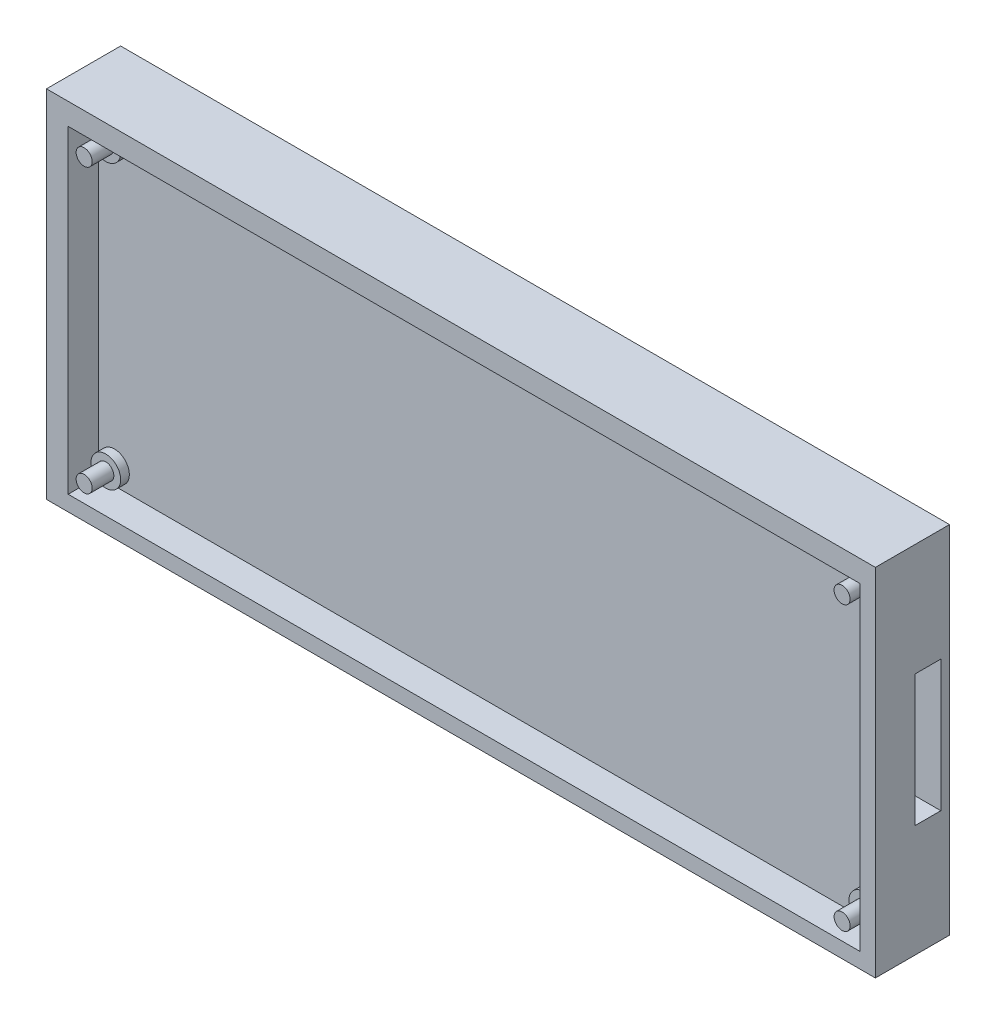
SolidWorks part; units mm, degrees
ref_plane "Front Plane" through (0, 0, 0) normal (0, 0, 1) x (1, 0, 0)
ref_plane "Top Plane" through (0, 0, 0) normal (0, 1, 0) x (1, 0, 0)
ref_plane "Right Plane" through (0, 0, 0) normal (1, 0, 0) x (0, 0, -1)
sketch "Sketch1" plane through (0, 0, 0) normal (0, 0, 1) x (1, 0, 0)
  line L1 (-101.6249, 55.2181) -> (80.9503, 55.2181)
  line L2 (-101.6249, 55.2181) -> (-101.6249, -18.2387)
  line L3 (-101.6249, -18.2387) -> (80.9503, -18.2387)
  line L4 (80.9503, 55.2181) -> (80.9503, -18.2387)
extrude "Boss-Extrude1" add sketch "Sketch1" along normal blind 5 and the other way blind 0.0932
sketch "Sketch2" plane through (0, 0, 5) normal (0, 0, 1) x (1, 0, 0)
  circle A0 centre (-97.9419, 50.9509) radius 3.4164
  circle A1 centre (76.8101, 50.9509) radius 3.4164
  circle A2 centre (76.8101, -14.2763) radius 3.4164
  circle A3 centre (-97.9419, -14.2763) radius 3.4164
extrude "Boss-Extrude2" add sketch "Sketch2" along normal blind 7
sketch "Sketch3" plane through (0, 0, 12) normal (0, 0, 1) x (1, 0, 0)
  circle A0 centre (-97.9419, 50.9509) radius 1.85
  circle A1 centre (-97.9419, -14.2763) radius 1.85
  circle A2 centre (76.8101, -14.2763) radius 1.85
  circle A3 centre (76.8101, 50.9509) radius 1.85
extrude "Boss-Extrude3" add sketch "Sketch3" along normal blind 5
sketch "Sketch4" plane through (0, 0, 5) normal (0, 0, 1) x (1, 0, 0)
  line L0 (-101.6249, 55.2181) -> (-106.6249, 60.2181) construction
  line L1 (80.9503, 55.2181) -> (-101.6249, 55.2181) construction
  line L2 (-101.6249, 55.2181) -> (-101.6249, -18.2387) construction
  line L3 (80.9503, -18.2387) -> (84.4858, -21.7743) construction
  line L4 (80.9503, -18.2387) -> (80.9503, 55.2181) construction
  line L5 (-101.6249, -18.2387) -> (80.9503, -18.2387) construction
  line L7 (-106.6249, 60.2181) -> (84.4858, 60.2181)
  line L8 (-106.6249, 60.2181) -> (-106.6249, -21.7743)
  line L9 (-106.6249, -21.7743) -> (84.4858, -21.7743)
  line L10 (84.4858, 60.2181) -> (84.4858, -21.7743)
  line L11 (-101.6249, 55.2181) -> (80.9503, 55.2181)
  line L12 (-101.6249, 55.2181) -> (-101.6249, -18.2387)
  line L13 (-101.6249, -18.2387) -> (80.9503, -18.2387)
  line L14 (80.9503, 55.2181) -> (80.9503, -18.2387)
  point P8 (0, 0)
  dimension "D1" = 5
  dimension "D2" = 135
  dimension "D3" = 5
  dimension "D4" = 135
extrude "Boss-Extrude4" add sketch "Sketch4" along normal up to surface (12 mm away) separate body up to face at (-96.0919, -14.2763, 17)
sketch "Sketch5" plane through (0, 0, 5) normal (0, 0, -1) x (-1, 0, 0)
  line L0 (-84.4858, -21.7743) -> (-84.4858, 60.2181) construction
  line L1 (-84.4858, 60.2181) -> (106.6249, 60.2181)
  line L2 (-84.4858, 60.2181) -> (-84.4858, -21.7743)
  line L3 (-84.4858, -21.7743) -> (106.6249, -21.7743)
  line L4 (106.6249, 60.2181) -> (106.6249, -21.7743)
  line L5 (-84.4858, 60.2181) -> (106.6249, 60.2181) construction
  line L6 (106.6249, -21.7743) -> (-84.4858, -21.7743) construction
extrude "Boss-Extrude5" add sketch "Sketch5" along normal up to surface (5.0932 mm away) up to face at (-10.3373, 18.4897, -0.0932)
sketch "Sketch6" plane through (0, 0, -0.0932) normal (0, 0, -1) x (-1, 0, 0)
  line L0 (-84.4858, 60.2181) -> (-84.4858, 19.2219) construction
  line L1 (-84.4858, 60.2181) -> (106.6249, 60.2181) construction
  line L2 (-84.4858, -21.7743) -> (-84.4858, 60.2181) construction
  line L3 (-84.4858, 34.3607) -> (-84.4858, 4.0831)
  line L7 (-56.8643, 4.0831) -> (-56.8643, 34.3607)
  line L10 (-66.23, 4.0831) -> (-66.23, 0.2715)
  line L11 (-66.23, 0.2715) -> (-63.5106, 0.2715)
  line L12 (-63.5106, 0.2715) -> (-56.8643, 4.0831)
  line L13 (-56.8643, 19.2219) -> (-67.8812, 19.2219) construction
  line L14 (-63.5106, 38.1723) -> (-56.8643, 34.3607)
  line L15 (-66.23, 38.1723) -> (-63.5106, 38.1723)
  line L16 (-66.23, 34.3607) -> (-66.23, 38.1723)
  line L17 (-66.23, 34.3607) -> (-84.4858, 34.3607)
  line L18 (-66.23, 4.0831) -> (-84.4858, 4.0831)
sketch "Sketch7" plane through (0, 0, 5) normal (0, 0, 1) x (1, 0, 0)
  line L0 (-101.6249, 55.2181) -> (-101.6249, -18.2387) construction
  line L1 (-101.6249, 55.2181) -> (80.9503, 55.2181)
  line L2 (-101.6249, 55.2181) -> (-101.6249, -18.2387)
  line L3 (-101.6249, -18.2387) -> (80.9503, -18.2387)
  line L4 (80.9503, 55.2181) -> (80.9503, -18.2387)
  line L5 (80.9503, 55.2181) -> (-101.6249, 55.2181) construction
  line L6 (-101.6249, -18.2387) -> (80.9503, -18.2387) construction
extrude "Boss-Extrude7" add sketch "Sketch7" along normal blind 5
extrude "Cut-Extrude1" cut sketch "Sketch6" against normal blind 6 from offset 2 offset against normal yes
ref_plane "Plane1" through (-11.0695, 0, 0) normal (1, 0, 0) x (0, 0, -1)
mirror "Mirror1" about plane through (-11.0695, 0, 0) normal (1, 0, 0) of "Cut-Extrude1"
